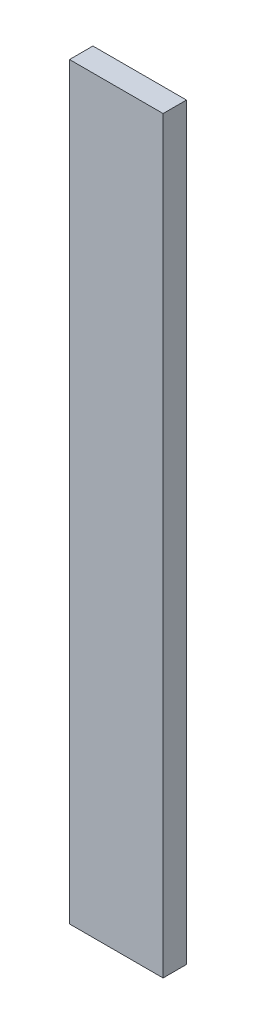
SolidWorks part; units mm, degrees
material "Pin"
ref_plane "Front" through (0, 0, 0) normal (0, 0, 1) x (1, 0, 0)
ref_plane "Top" through (0, 0, 0) normal (0, 1, 0) x (1, 0, 0)
ref_plane "Right" through (0, 0, 0) normal (1, 0, 0) x (0, 0, -1)
sketch "Esquisse1" plane through (0, 0, 0) normal (0, 0, 1) x (1, 0, 0)
  line L1 (-12.7, 101.6) -> (12.7, 101.6)
  line L2 (-12.7, 101.6) -> (-12.7, -101.6)
  line L3 (-12.7, -101.6) -> (12.7, -101.6)
  line L4 (12.7, 101.6) -> (12.7, -101.6)
  line L5 (-12.7, 101.6) -> (12.7, -101.6) construction
  line L6 (-12.7, -101.6) -> (12.7, 101.6) construction
  point P0 (0, 0)
  dimension "D1" = 203.2
  dimension "D2" = 25.4
extrude "Boss.-Extru.1" add sketch "Esquisse1" along normal blind 6.35
